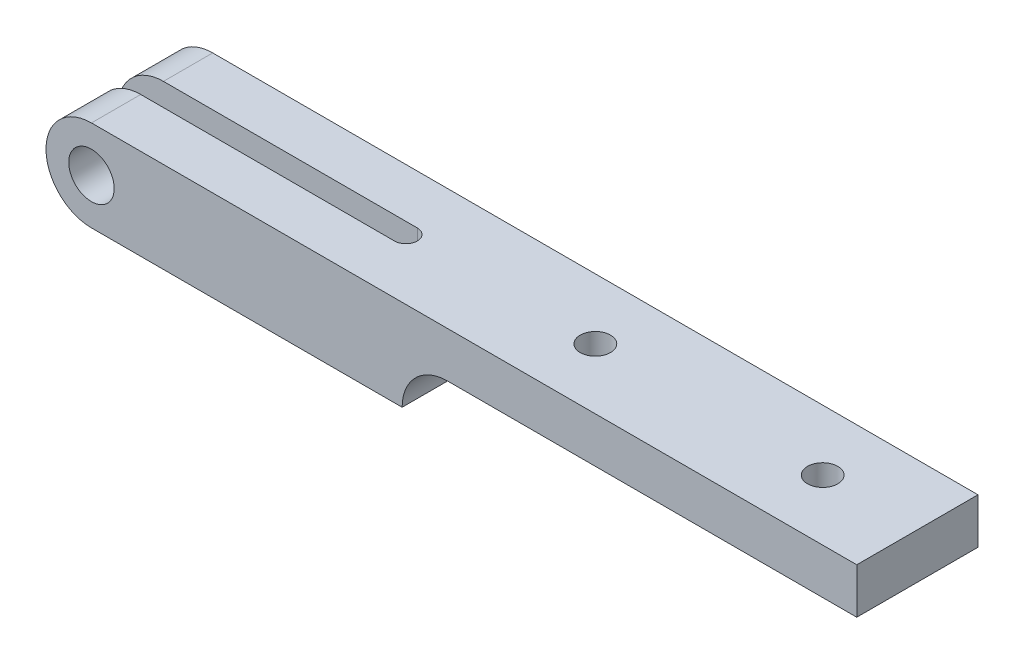
SolidWorks part; units mm, degrees
material "Alumina"
ref_plane "Front Plane" through (0, 0, 0) normal (0, 0, 1) x (1, 0, 0)
ref_plane "Top Plane" through (0, 0, 0) normal (0, 1, 0) x (1, 0, 0)
ref_plane "Right Plane" through (0, 0, 0) normal (1, 0, 0) x (0, 0, -1)
sketch "Sketch2" plane through (0, 0, 0) normal (0, 0, 1) x (1, 0, 0)
  line L0 (0, 6) -> (101, 6)
  line L1 (101, 0) -> (101, 6)
  line L2 (101, 0) -> (47, 0)
  line L3 (0, -6) -> (41, -6)
  circle A0 centre (0, 0) radius 3
  arc A1 (0, 6) -> (0, -6) centre (0, 0) ccw
  arc A2 (41, -6) -> (47, 0) centre (47, -6) cw
  point P3 (0, 0)
  point P11 (0, 0)
  point P12 (0, 0)
  point P13 (0, 0)
  dimension "D1" = 6
  dimension "D2" = 6
  dimension "D3" = 6
  dimension "D4" = 41
  dimension "D5" = 60
  dimension "D6" = 6
extrude "Boss-Extrude1" add sketch "Sketch2" along normal mid plane 16 contours L3 A2 L2 L1 L0 A1 A0
sketch "Sketch3" plane through (0, 6, 0) normal (0, 1, 0) x (1, 0, 0)
  line L0 (0, 0) -> (-50000, 0) construction
  line L1 (-6, 8) -> (-6, -8) construction
  line L2 (33.5, -1.5) -> (-6, -1.5)
  line L4 (33.5, 1.5) -> (-6, 1.5)
  line L5 (-6, -1.5) -> (-6, 1.5)
  line L6 (33.5, -1.5) -> (-6, 1.5) construction
  line L7 (33.5, 1.5) -> (-6, -1.5) construction
  line L8 (101, -8) -> (101, 8) construction
  arc A0 (33.5, 1.5) -> (33.5, -1.5) centre (33.5, 0) cw
  circle A1 centre (58.5, 0) radius 2
  circle A2 centre (88.5, 0) radius 2
  point P3 (13.75, 0)
  point P11 (35, 0)
  dimension "D3" = 1.5
  dimension "D6" = 4
  dimension "D1" = 3
  dimension "D2" = 41
  dimension "D4" = 30
  dimension "D5" = 12.5
extrude "Cut-Extrude1" cut sketch "Sketch3" against normal through all
